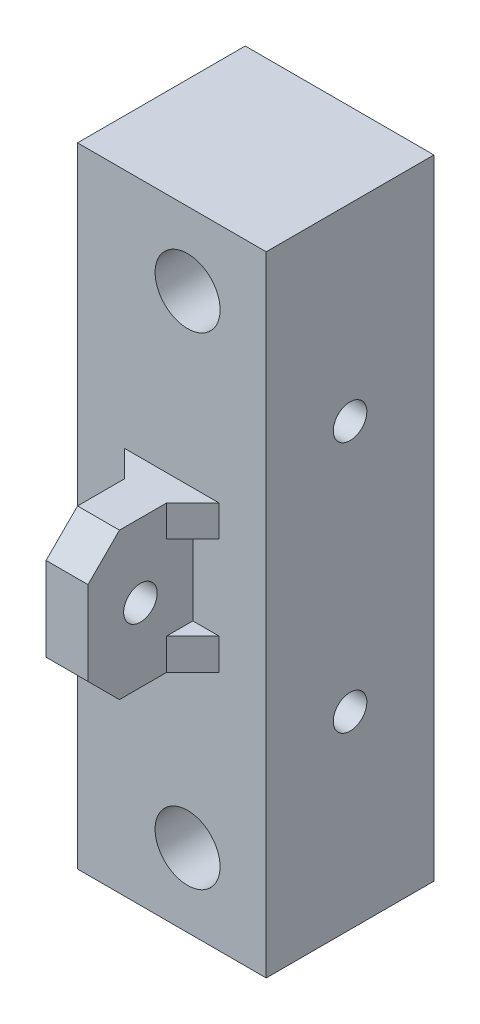
SolidWorks part; units mm, degrees
ref_plane "Front Plane" through (0, 0, 0) normal (0, 0, 1) x (1, 0, 0)
ref_plane "Top Plane" through (0, 0, 0) normal (0, 1, 0) x (1, 0, 0)
ref_plane "Right Plane" through (0, 0, 0) normal (1, 0, 0) x (0, 0, -1)
sketch "Sketch1" plane through (0, 0, 0) normal (0, 0, 1) x (1, 0, 0)
  line L1 (-9, 30) -> (9, 30)
  line L2 (-9, 30) -> (-9, -30)
  line L3 (-9, -30) -> (9, -30)
  line L4 (9, 30) -> (9, -30)
  line L5 (-9, 30) -> (9, -30) construction
  line L6 (-9, -30) -> (9, 30) construction
  point P0 (0, 0)
  dimension "D1" = 18
  dimension "D2" = 60
extrude "Boss-Extrude1" add sketch "Sketch1" along normal blind 16
sketch "Sketch2" plane through (0, 0, 16) normal (0, 0, 1) x (1, 0, 0)
  line L0 (9, 30) -> (-9, 30) construction
  line L1 (-9, -30) -> (9, -30) construction
  line L3 (9, -30) -> (9, 30) construction
  circle A0 centre (1.5, 23) radius 3.1
  circle A1 centre (1.5, -23) radius 3.1
  point P8 (0, 0)
  point P9 (5.2599, 23)
  dimension "D1" = 7
  dimension "D2" = 7
  dimension "D3" = 6.2
  dimension "D4" = 6.2
  dimension "D5" = 7.5
extrude "Cut-Extrude1" cut sketch "Sketch2" against normal through all
sketch "Sketch3" plane through (9, 0, 0) normal (1, 0, 0) x (0, 0, -1)
  line L0 (-16, 30) -> (0, 30) construction
  line L1 (0, -30) -> (0, 30) construction
  line L2 (-16, -30) -> (0, -30) construction
  circle A0 centre (-8, 12) radius 1.6
  circle A1 centre (-8, -12) radius 1.6
  dimension "D1" = 18
  dimension "D2" = 3.2
  dimension "D3" = 3.2
  dimension "D4" = 8
  dimension "D6" = 18
  dimension "D5" = 8
extrude "Cut-Extrude2" cut sketch "Sketch3" against normal through all
sketch "Sketch4" plane through (0, 0, 16) normal (0, 0, 1) x (1, 0, 0)
  line L1 (-2, 7) -> (2, 7)
  line L2 (-2, 7) -> (-2, -7)
  line L3 (-2, -7) -> (2, -7)
  line L4 (2, 7) -> (2, -7)
  line L5 (-2, 7) -> (2, -7) construction
  line L6 (-2, -7) -> (2, 7) construction
  point P0 (0, 0)
  dimension "D1" = 14
  dimension "D2" = 4
extrude "Boss-Extrude2" add sketch "Sketch4" along normal blind 10
sketch "Sketch5" plane through (2, 0, 0) normal (1, 0, 0) x (0, 0, -1)
  line L0 (-26, -7) -> (-26, 7) construction
  circle A0 centre (-21, 0) radius 1.6
  dimension "D1" = 3.2
  dimension "D2" = 5
extrude "Cut-Extrude3" cut sketch "Sketch5" against normal blind 10
chamfer "Chamfer1" distance 3 angle 45 2 edges at (0, -7, 26) (0, 7, 26)
sketch "Sketch6" plane through (0, 7, 0) normal (0, 1, 0) x (1, 0, 0)
  line L0 (2, -16) -> (4.5, -16)
  line L1 (4.5, -16) -> (2, -18.5)
  line L2 (2, -23) -> (2, -16) construction
  line L3 (2, -18.5) -> (2, -16)
  line L4 (0, -16) -> (0, -19.4616) construction
  line L5 (2, -16) -> (-2, -16) construction
  line L7 (-4.5, -16) -> (-2, -18.5)
  line L8 (-2, -16) -> (-4.5, -16)
  line L9 (-2, -18.5) -> (-2, -16)
  dimension "D1" = 2.5
  dimension "D2" = 2.5
  dimension "D3" = 2.5
  dimension "D4" = 2.5
extrude "Boss-Extrude3" add sketch "Sketch6" against normal blind 3
sketch "Sketch7" plane through (0, -7, 0) normal (0, -1, 0) x (1, 0, 0)
  line L0 (-2, 16) -> (-2, 18.5)
  line L1 (-2, 23) -> (-2, 16) construction
  line L2 (-2, 18.5) -> (-4.5, 16)
  line L3 (-4.5, 16) -> (-2, 16)
  line L4 (2, 16) -> (2, 18.5)
  line L5 (2, 23) -> (2, 16) construction
  line L6 (2, 18.5) -> (4.5, 16)
  line L7 (4.5, 16) -> (2, 16)
  dimension "D1" = 2.5
  dimension "D2" = 2.5
  dimension "D3" = 2.5
  dimension "D4" = 2.5
extrude "Boss-Extrude4" add sketch "Sketch7" against normal blind 3
